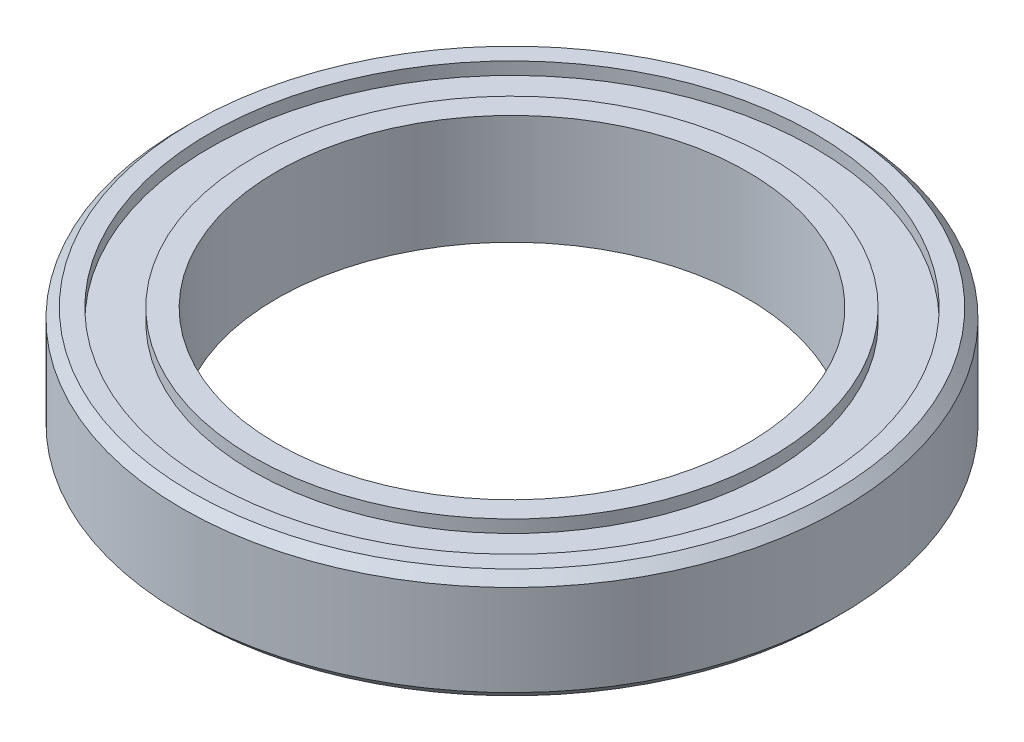
SolidWorks part; units mm, degrees
ref_plane "前视基准面" through (0, 0, 0) normal (0, 0, 1) x (1, 0, 0)
ref_plane "上视基准面" through (0, 0, 0) normal (0, 1, 0) x (1, 0, 0)
ref_plane "右视基准面" through (0, 0, 0) normal (1, 0, 0) x (0, 0, -1)
sketch "草图1" plane through (0, 0, 0) normal (0, 1, 0) x (1, 0, 0)
  circle A0 centre (0, 0) radius 21
  circle A1 centre (0, 0) radius 15
  dimension "D1" = 42
  dimension "D2" = 30
extrude "凸台-拉伸1" add sketch "草图1" along normal blind 7
chamfer "倒角1" distance 0.6 angle 45 2 edges at (0, 0, 21) (0, 7, 21)
sketch "草图2" plane through (0, 7, 0) normal (0, 1, 0) x (1, 0, 0)
  circle A0 centre (0, 0) radius 16.5
  circle A1 centre (0, 0) radius 19.25
  dimension "D1" = 33
  dimension "D2" = 38.5
extrude "切除-拉伸1" cut sketch "草图2" against normal blind 0.8
sketch "草图3" plane through (0, 0, 0) normal (0, -1, 0) x (1, 0, 0)
  circle A1 centre (0, 0) radius 19.25
  circle A2 centre (0, 0) radius 19.25
  circle A3 centre (0, 0) radius 16.5
  circle A4 centre (0, 0) radius 16.5
  dimension "D1" = 0
  dimension "D2" = 0
extrude "切除-拉伸3" cut sketch "草图3" against normal blind 0.8
